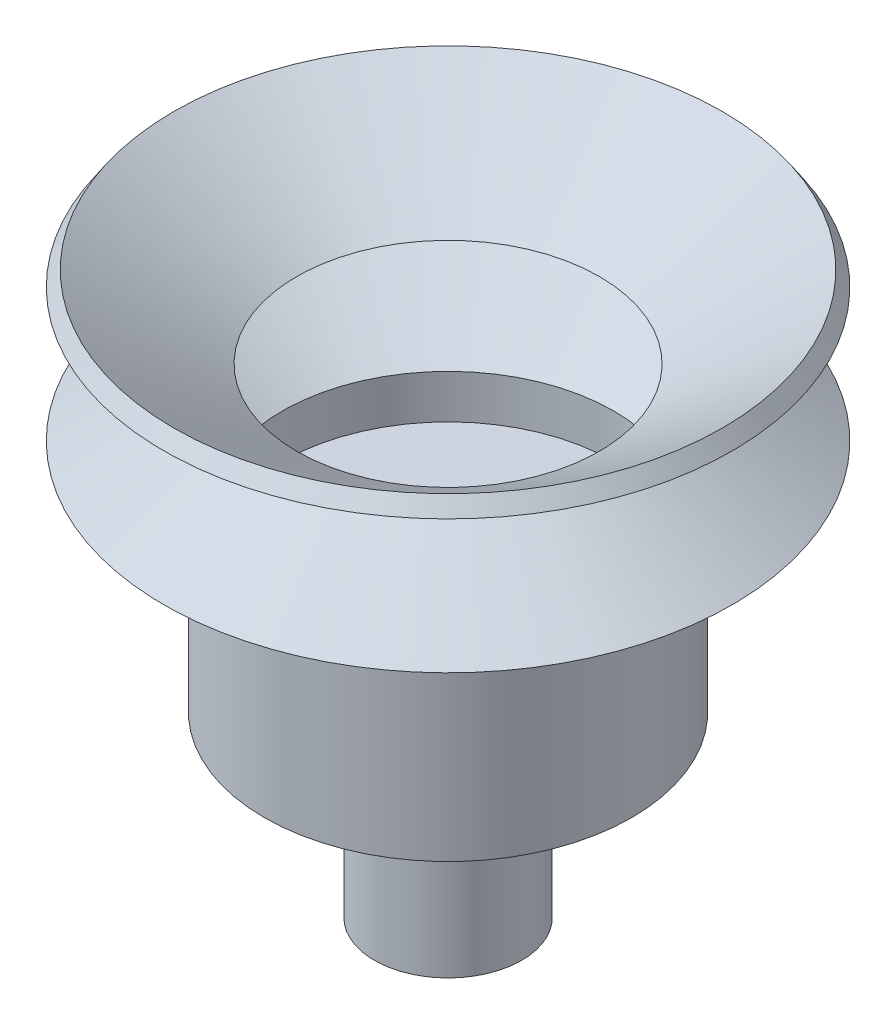
SolidWorks part; units mm, degrees
ref_plane "Plan de face" through (0, 0, 0) normal (0, 0, 1) x (1, 0, 0)
ref_plane "Plan de dessus" through (0, 0, 0) normal (0, 1, 0) x (1, 0, 0)
ref_plane "Plan de droite" through (0, 0, 0) normal (1, 0, 0) x (0, 0, -1)
sketch "Esquisse1" plane through (0, 0, 0) normal (0, 0, 1) x (1, 0, 0)
  line L0 (0, 0) -> (0, 30.0286) construction
  line L1 (0, 0) -> (8.2271, 0)
  line L2 (8.2271, 0) -> (8.2271, 7.52)
  line L3 (8.2271, 7.52) -> (12.7271, 10.5049)
  line L4 (12.7271, 10.5049) -> (8.2271, 13.4899)
  line L5 (8.2271, 13.4899) -> (12.7271, 16.4749)
  line L6 (12.7271, 16.4749) -> (12.2849, 17.1415)
  line L7 (12.2849, 17.1415) -> (6.7799, 13.4899)
  line L8 (6.7799, 13.4899) -> (11.2799, 10.5049)
  line L9 (11.2799, 10.5049) -> (7.4271, 7.9493)
  line L10 (7.4271, 7.9493) -> (7.4271, 5.9899)
  line L11 (7.4271, 5.9899) -> (0, 5.9899)
  line L12 (0, 5.9899) -> (0, 0)
  line L13 (11.2799, 10.5049) -> (11.7221, 9.8383) construction
  line L14 (11.2799, 10.5049) -> (11.7221, 11.1716) construction
  line L15 (8.2271, 7.52) -> (7.4271, 7.52) construction
  point P20 (0, 0)
  point P21 (3.6741, 5.7545)
  point P22 (0, 0)
  dimension "D1" = 8.2271
  dimension "D2" = 7.52
  dimension "D3" = 12.7271
  dimension "D4" = 8.2271
  dimension "D5" = 5.4
  dimension "D6" = 0.8
  dimension "D7" = 0.8
  dimension "D8" = 7.5
revolve "Révolution1" add sketch "Esquisse1" angle 360 about L0
sketch "Esquisse2" plane through (0, 0, 0) normal (0, -1, 0) x (1, 0, 0)
  circle A0 centre (0, 0) radius 3.3
  dimension "D1" = 6.6
extrude "Boss.-Extru.1" add sketch "Esquisse2" along normal blind 8
